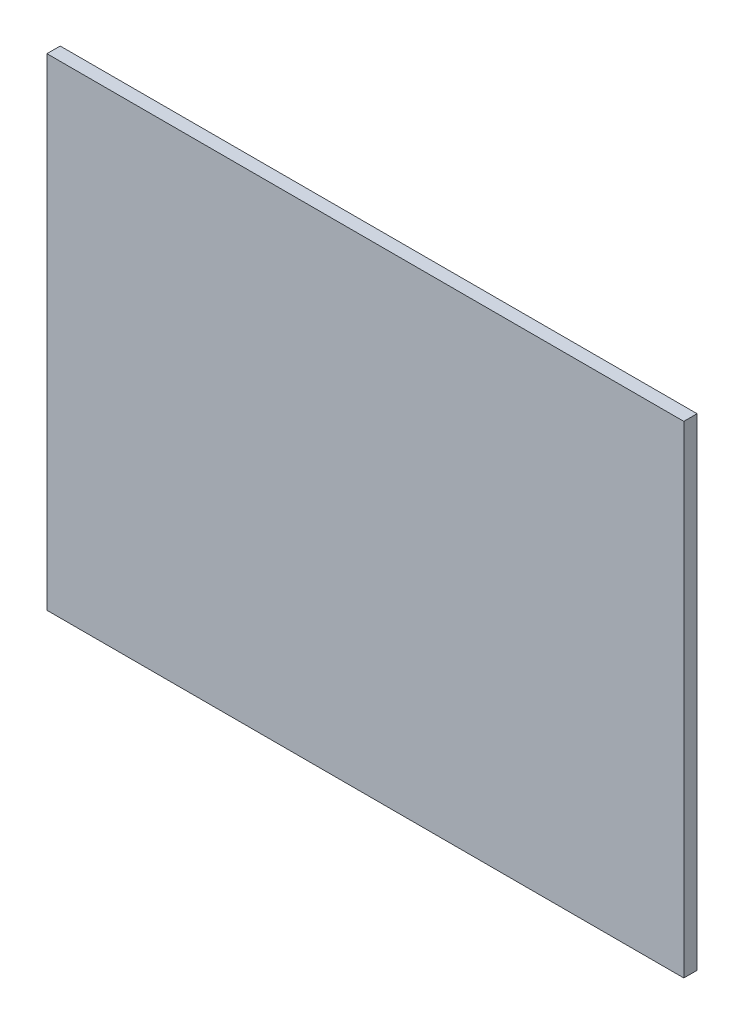
SolidWorks part; units mm, degrees
ref_plane "Front Plane" through (0, 0, 0) normal (0, 0, 1) x (1, 0, 0)
ref_plane "Top Plane" through (0, 0, 0) normal (0, 1, 0) x (1, 0, 0)
ref_plane "Right Plane" through (0, 0, 0) normal (1, 0, 0) x (0, 0, -1)
sketch "Sketch1" plane through (0, 0, 0) normal (0, 1, 0) x (1, 0, 0)
  line L0 (457.2, 298.45) -> (-457.2, 298.45)
  line L1 (-476.25, 298.45) -> (476.25, 298.45) construction
  line L2 (-457.2, 298.45) -> (-457.2, 279.4)
  line L3 (-457.2, 279.4) -> (457.2, 279.4)
  line L4 (457.2, 279.4) -> (457.2, 298.45)
  dimension "D1" = 19.05
  dimension "D2" = 19.05
  dimension "D3" = 19.05
extrude "Boss-Extrude1" add sketch "Sketch1" along normal offset from surface (692.15 mm away) 19.05
